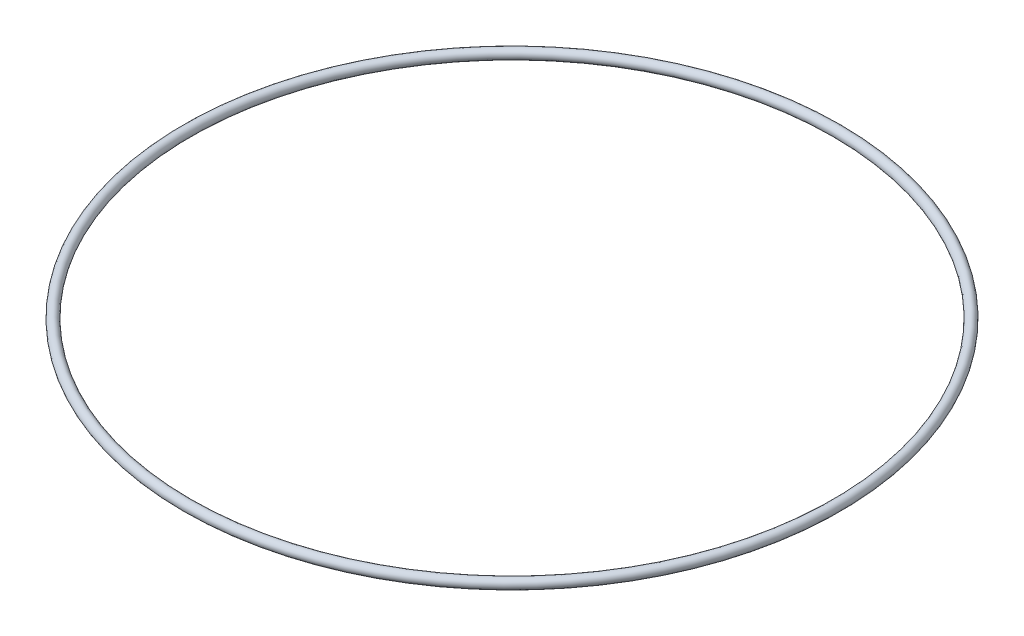
SolidWorks part; units mm, degrees
ref_plane "Front Plane" through (0, 0, 0) normal (0, 0, 1) x (1, 0, 0)
ref_plane "Top Plane" through (0, 0, 0) normal (0, 1, 0) x (1, 0, 0)
ref_plane "Right Plane" through (0, 0, 0) normal (1, 0, 0) x (0, 0, -1)
sketch "Sketch1" plane through (0, 0, 0) normal (0, 0, 1) x (1, 0, 0)
  line L0 (0, -50) -> (0, 50) construction
  circle A0 centre (197, 0) radius 3
revolve "Revolve1" add sketch "Sketch1" angle 360 about L0
